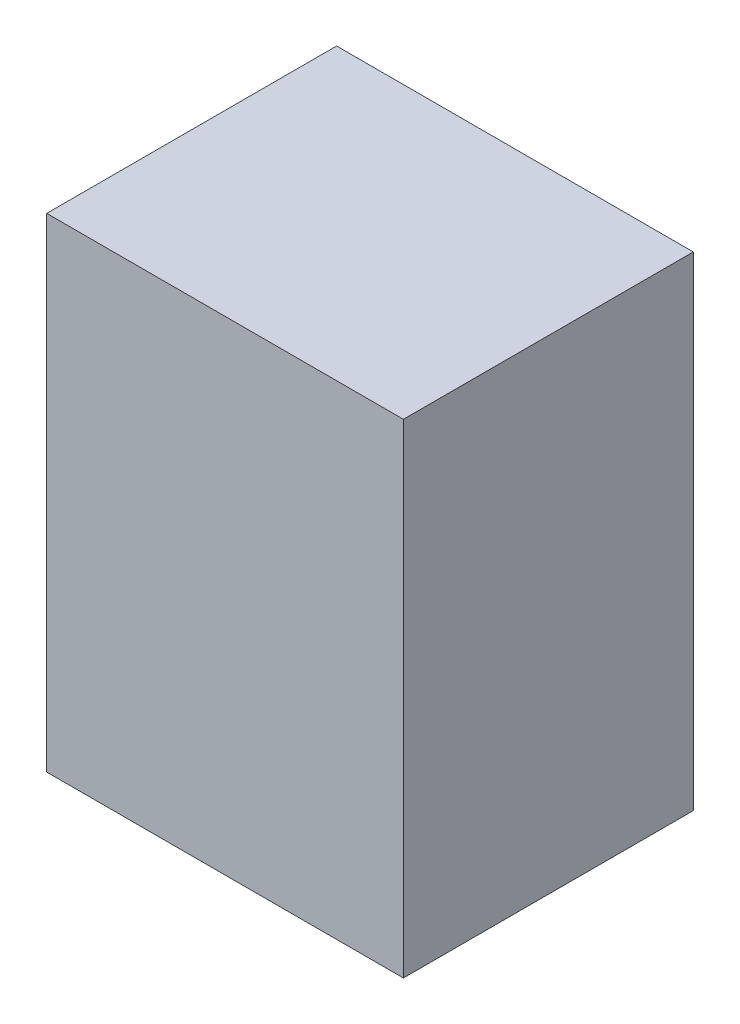
SolidWorks part; units mm, degrees
ref_plane "Front Plane" through (0, 0, 0) normal (0, 0, 1) x (1, 0, 0)
ref_plane "Top Plane" through (0, 0, 0) normal (0, 1, 0) x (1, 0, 0)
ref_plane "Right Plane" through (0, 0, 0) normal (1, 0, 0) x (0, 0, -1)
sketch "Sketch1" plane through (0, 0, 0) normal (0, 0, 1) x (1, 0, 0)
  line L0 (-44.6155, 65.27) -> (-53.9355, 65.27) construction
  line L1 (-53.7355, 77.5714) -> (-44.8155, 77.5714)
  line L2 (-53.7355, 77.5714) -> (-53.7355, 65.47)
  line L3 (-53.7355, 65.47) -> (-44.8155, 65.47)
  line L4 (-44.8155, 77.5714) -> (-44.8155, 65.47)
  line L5 (-44.6155, 77.7714) -> (-44.6155, 65.27) construction
  line L6 (-44.6155, 77.7714) -> (-53.9355, 77.7714) construction
  line L7 (-53.9355, 65.27) -> (-53.9355, 77.7714) construction
  dimension "D1" = 0.2
  dimension "D2" = 0.2
  dimension "D3" = 0.2
  dimension "D4" = 0.2
extrude "Boss-Extrude1" add sketch "Sketch1" along normal blind 7.25 contours L2 L3 L4 L1
shell "Shell1" thickness 0.5
equation "\"D2@Sketch1\"=\"D3@Sketch1\""
equation "\"D1@Sketch1\"=\"D3@Sketch1\""
equation "\"D4@Sketch1\"=\"D3@Sketch1\""
